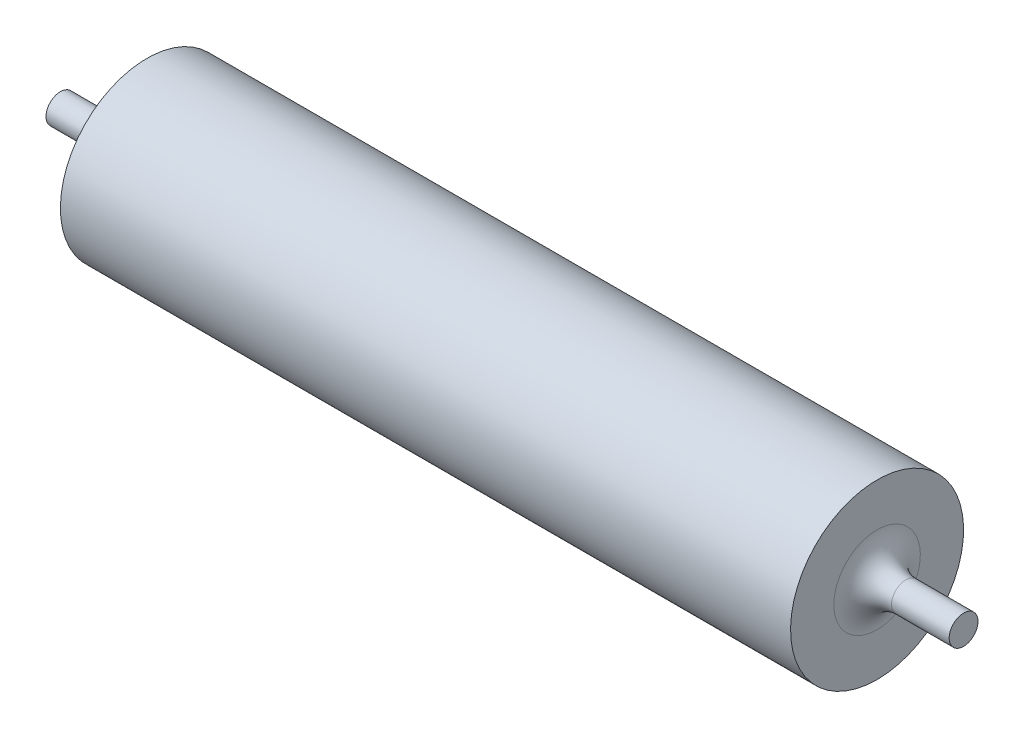
SolidWorks part; units mm, degrees
ref_plane "Plan de face" through (0, 0, 0) normal (0, 0, 1) x (1, 0, 0)
ref_plane "Plan de dessus" through (0, 0, 0) normal (0, 1, 0) x (1, 0, 0)
ref_plane "Plan de droite" through (0, 0, 0) normal (1, 0, 0) x (0, 0, -1)
sketch "Esquisse1" plane through (0, 0, 0) normal (0, 0, 1) x (1, 0, 0)
  line L0 (-81.1413, 0) -> (75.2437, 0) construction
  line L1 (-78.3, 0) -> (-78.3, 2.5)
  line L2 (-78.3, 2.5) -> (-63.3, 2.5)
  line L3 (-63.3, 2.5) -> (-63.3, 15)
  line L4 (-63.3, 15) -> (63.3, 15)
  line L5 (-78.3, 0) -> (78.3, 0)
  line L6 (0, 15) -> (0, 0) construction
  line L7 (63.3, 2.5) -> (63.3, 15)
  line L8 (78.3, 2.5) -> (63.3, 2.5)
  line L9 (78.3, 0) -> (78.3, 2.5)
  dimension "D1" = 78.3
  dimension "D2" = 15
  dimension "D3" = 2.5
  dimension "D4" = 15
revolve "Révolution1" add sketch "Esquisse1" angle 360 about L5
fillet "Congé1" radius 5 2 edges at (63.3, -2.5, 0) (-63.3, -2.5, 0)
